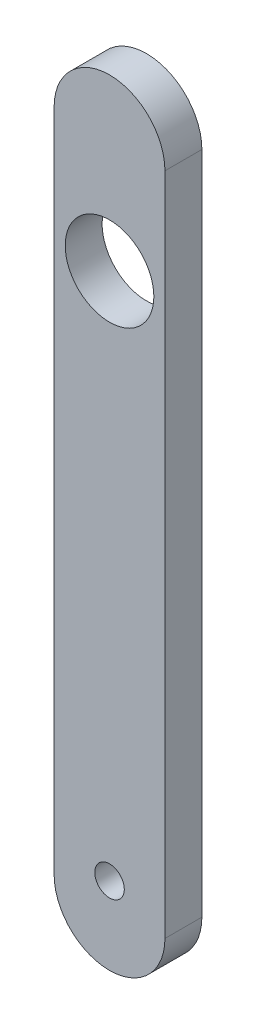
SolidWorks part; units mm, degrees
ref_plane "Plano frontal" through (0, 0, 0) normal (0, 0, 1) x (1, 0, 0)
ref_plane "Plano superior" through (0, 0, 0) normal (0, 1, 0) x (1, 0, 0)
ref_plane "Plano direito" through (0, 0, 0) normal (1, 0, 0) x (0, 0, -1)
sketch "Esboço1" plane through (0, 0, 0) normal (0, 0, 1) x (1, 0, 0)
  line L0 (15, 74.5) -> (0, 74.5) construction
  line L2 (0, 0) -> (0, 90)
  line L4 (15, 0) -> (15, 90)
  arc A0 (0, 0) -> (15, 0) centre (7.5, 0) ccw
  arc A1 (0, 90) -> (15, 90) centre (7.5, 90) cw
  circle A2 centre (7.5, 3) radius 2
  circle A3 centre (7.5, 74.5) radius 6
  dimension "D3" = 4
  dimension "D5" = 12
  dimension "D1" = 15
  dimension "D2" = 90
  dimension "D4" = 3
  dimension "D7" = 74.5
extrude "Ressalto-extrusão1" add sketch "Esboço1" along normal blind 5
